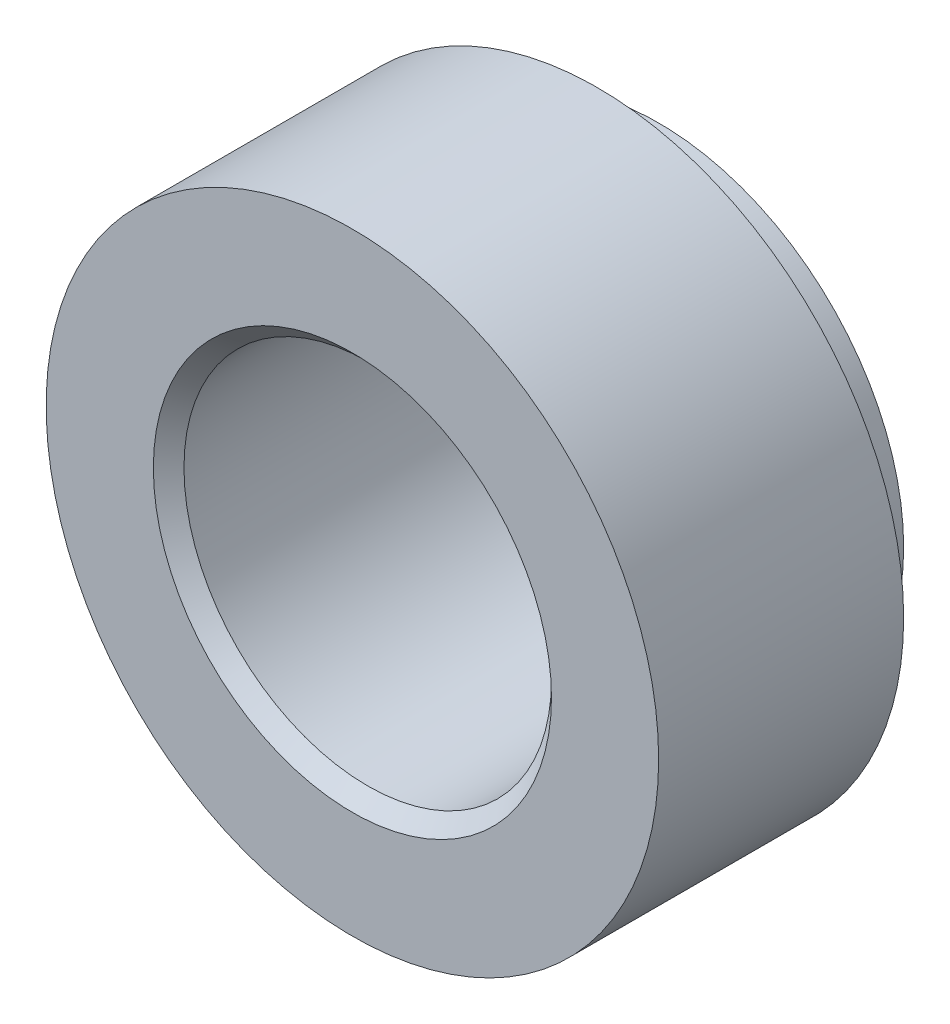
SolidWorks part; units mm, degrees
material "Tin Bearing Bronze"
ref_plane "Front Plane" through (0, 0, 0) normal (0, 0, 1) x (1, 0, 0)
ref_plane "Top Plane" through (0, 0, 0) normal (0, 1, 0) x (1, 0, 0)
ref_plane "Right Plane" through (0, 0, 0) normal (1, 0, 0) x (0, 0, -1)
sketch "Sketch1" plane through (0, 0, 0) normal (1, 0, 0) x (0, 0, -1)
  line L0 (0, 0) -> (23.9988, 0) construction
  line L1 (0, 19.05) -> (0, 31.75)
  line L2 (0, 31.75) -> (25.4, 31.75)
  line L3 (25.4, 31.75) -> (25.4, 25.4)
  line L4 (25.4, 25.4) -> (31.75, 25.4)
  line L5 (31.75, 25.4) -> (31.75, 19.05)
  line L6 (31.75, 19.05) -> (0, 19.05)
  dimension "D1" = 31.75
  dimension "D2" = 6.35
  dimension "D3" = 50.8
  dimension "D4" = 63.5
  dimension "D5" = 38.1
revolve "Revolve1" add sketch "Sketch1" angle 360 about L0
chamfer "Chamfer1" distance 1.5875 angle 45 2 edges at (19.05, 0, -31.75) (19.05, 0, 0)
